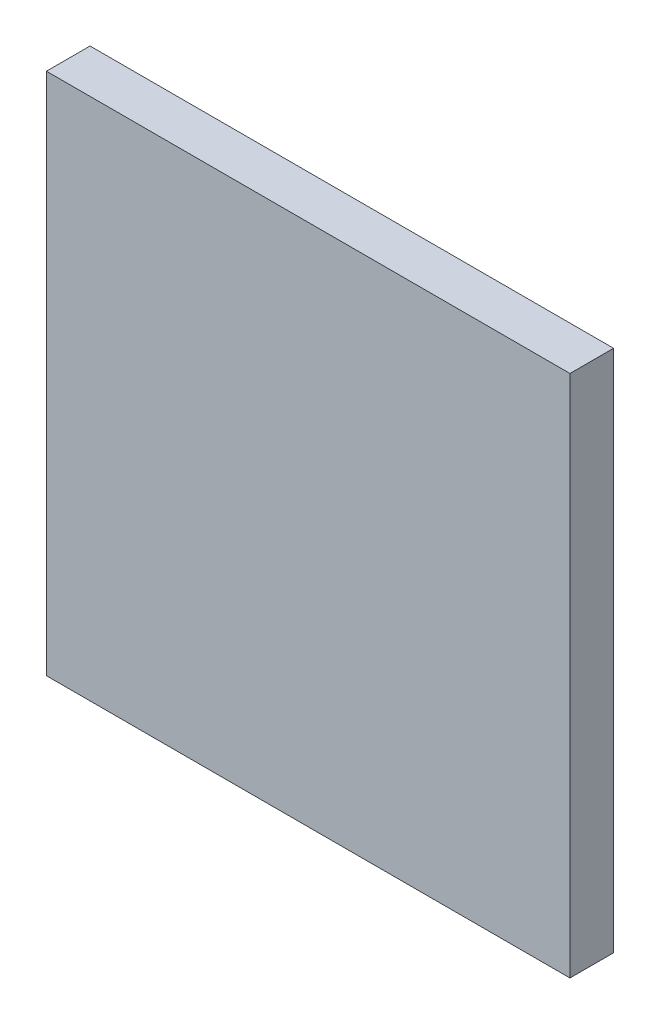
SolidWorks part; units mm, degrees
ref_plane "Front Plane" through (0, 0, 0) normal (0, 0, 1) x (1, 0, 0)
ref_plane "Top Plane" through (0, 0, 0) normal (0, 1, 0) x (1, 0, 0)
ref_plane "Right Plane" through (0, 0, 0) normal (1, 0, 0) x (0, 0, -1)
sketch "Sketch1" plane through (0, 0, 0) normal (0, 0, 1) x (1, 0, 0)
  line L1 (-55.283, 34.5283) -> (4.717, 34.5283)
  line L2 (-55.283, 34.5283) -> (-55.283, -25.4717)
  line L3 (-55.283, -25.4717) -> (4.717, -25.4717)
  line L4 (4.717, 34.5283) -> (4.717, -25.4717)
  dimension "D1" = 60
  dimension "D2" = 60
extrude "Boss-Extrude1" add sketch "Sketch1" along normal blind 5
